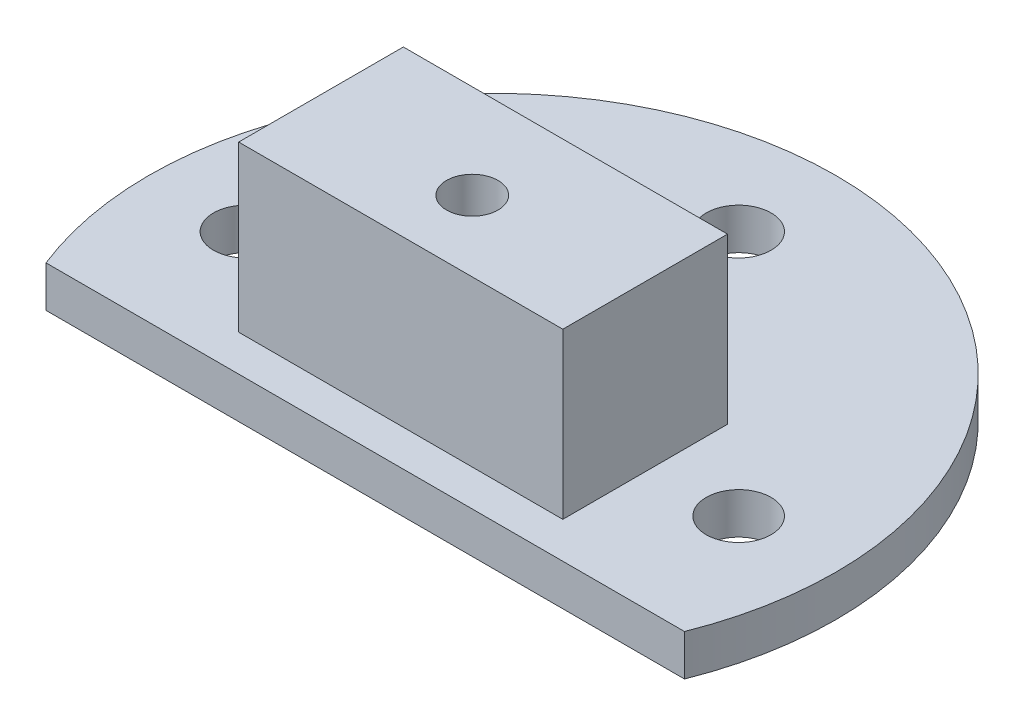
SolidWorks part; units mm, degrees
ref_plane "Front Plane" through (0, 0, 0) normal (0, 0, 1) x (1, 0, 0)
ref_plane "Top Plane" through (0, 0, 0) normal (0, 1, 0) x (1, 0, 0)
ref_plane "Right Plane" through (0, 0, 0) normal (1, 0, 0) x (0, 0, -1)
sketch "Sketch1" plane through (0, 0, 0) normal (0, 1, 0) x (1, 0, 0)
  line L0 (-49.2429, -19.5995) -> (49.2429, -19.5995)
  arc A0 (49.2429, -19.5995) -> (-49.2429, -19.5995) centre (0, 0) ccw
  circle A1 centre (-38, 0) radius 5
  circle A2 centre (38, 0) radius 5
  circle A3 centre (0, 38) radius 5
extrude "Boss-Extrude4" add sketch "Sketch1" along normal blind 6.35
sketch "Sketch5" plane through (0, 6.35, 0) normal (0, 1, 0) x (1, 0, 0)
  line L1 (-25.1229, -14) -> (24.8771, -14)
  line L2 (-25.1229, -14) -> (-25.1229, 11.4)
  line L3 (-25.1229, 11.4) -> (24.8771, 11.4)
  line L4 (24.8771, -14) -> (24.8771, 11.4)
extrude "Boss-Extrude5" add sketch "Sketch5" along normal blind 25.4 contours L2 L1 L4 L3
sketch "Sketch6" plane through (0, 31.75, 0) normal (0, 1, 0) x (1, 0, 0)
  circle A0 centre (0, -3.0895) radius 3.9688
extrude "Cut-Extrude1" cut sketch "Sketch6" against normal up to vertex
